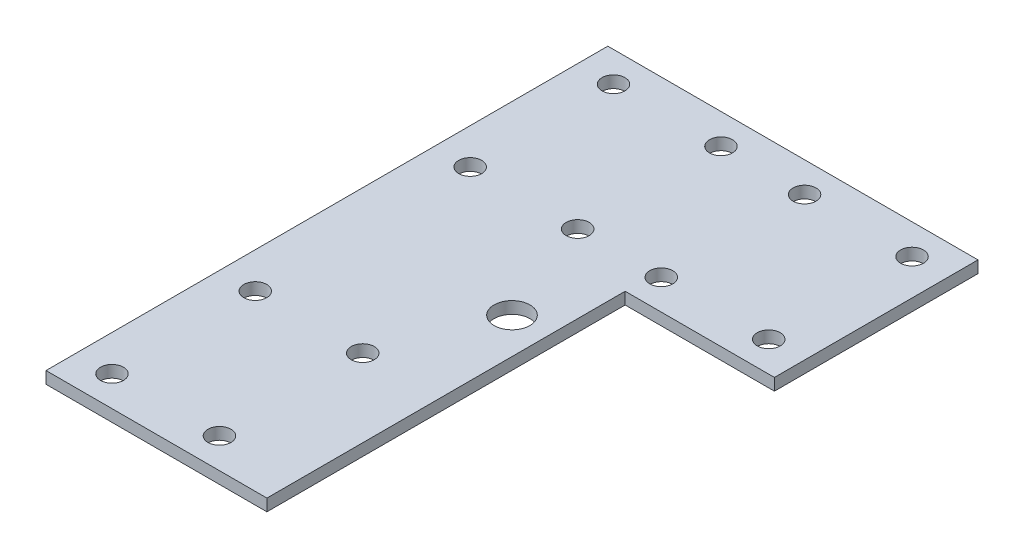
SolidWorks part; units mm, degrees
other "Markup1"
sketch "Sketch3" plane through (0, 2, 0) normal (0.5876, 0.8091, 0.0135) x (0.8092, -0.5875, -0.0087)
ref_plane "Front Plane" through (0, 0, 0) normal (0, 0, 1) x (1, 0, 0)
ref_plane "Top Plane" through (0, 0, 0) normal (0, 1, 0) x (1, 0, 0)
ref_plane "Right Plane" through (0, 0, 0) normal (1, 0, 0) x (0, 0, -1)
sketch "Sketch1" plane through (0, 0, 0) normal (0, 1, 0) x (1, 0, 0)
  line L0 (-56, 89.05) -> (-38, 89.05) construction
  line L1 (0, 0) -> (-62, 0)
  line L2 (0, 0) -> (0, 94.1)
  line L3 (0, 94.1) -> (-62, 94.1)
  line L4 (-62, 0) -> (-62, 94.1)
  line L5 (-56, 89.05) -> (-56, 65.05) construction
  line L6 (-56, 65.05) -> (-38, 65.05) construction
  line L7 (-56, 29.05) -> (-38, 29.05) construction
  line L8 (-56, 29.05) -> (-56, 5.05) construction
  line L9 (-56, 5.05) -> (-38, 5.05) construction
  line L10 (-24, 89.05) -> (-6, 89.05) construction
  line L11 (-24, 89.05) -> (-24, 65.05) construction
  line L12 (-24, 65.05) -> (-6, 65.05) construction
  circle A0 centre (-56, 89.05) radius 1.925
  circle A1 centre (-38, 89.05) radius 1.925
  circle A2 centre (-38, 65.05) radius 1.925
  circle A3 centre (-56, 65.05) radius 1.925
  circle A4 centre (-56, 29.05) radius 1.925
  circle A5 centre (-38, 29.05) radius 1.925
  circle A6 centre (-38, 5.05) radius 1.925
  circle A7 centre (-56, 5.05) radius 1.925
  circle A8 centre (-24, 89.05) radius 1.925
  circle A9 centre (-6, 89.05) radius 1.925
  circle A10 centre (-6, 65.05) radius 1.925
  circle A11 centre (-24, 65.05) radius 1.925
  point P29 (-56, 17.05)
  point P30 (-56, 77.05)
  dimension "D3" = 3.85
  dimension "D8" = 3.85
  dimension "D11" = 3.85
  dimension "D1" = 62
  dimension "D2" = 5.05
  dimension "D4" = 5.05
  dimension "D5" = 6
  dimension "D6" = 18
  dimension "D7" = 24
  dimension "D9" = 18
  dimension "D10" = 24
  dimension "D12" = 18
  dimension "D13" = 24
  dimension "D14" = 60
  dimension "D15" = 6
  dimension "D16" = 6
extrude "Boss-Extrude1" add sketch "Sketch1" along normal blind 2
sketch "Sketch2" plane through (0, 2, 0) normal (0, 1, 0) x (1, 0, 0)
  line L0 (0, 0) -> (0, 94.1) construction
  line L1 (-62, 0) -> (0, 0) construction
  circle A0 centre (-31, 47.05) radius 3
  dimension "D1" = 6
  dimension "D2" = 31
  dimension "D3" = 47.05
extrude "Cut-Extrude1" cut sketch "Sketch2" against normal through all
sketch "Sketch4" plane through (0, 2, 0) normal (0, 1, 0) x (1, 0, 0)
  line L0 (0, 60) -> (-25, 60)
  line L1 (0, 0) -> (0, 94.1) construction
  line L2 (-25, 60) -> (-25, 0)
  line L4 (0, 33.7766) -> (0, 60)
  line L5 (0, 94.1) -> (-62, 94.1) construction
  line L9 (0, 0) -> (0, 33.7766)
  line L10 (-62, 0) -> (0, 0) construction
  line L11 (0, 0) -> (-25, 0)
  dimension "D1" = 26.2234
  dimension "D2" = 34.1
  dimension "D3" = 25
extrude "Cut-Extrude2" cut sketch "Sketch4" against normal through all
